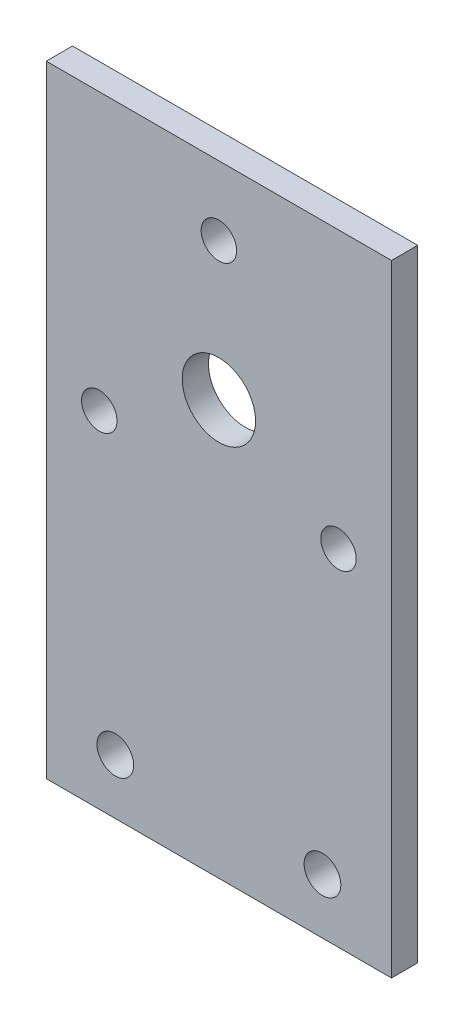
SolidWorks part; units mm, degrees
material "1060 Alloy"
ref_plane "Front Plane" through (0, 0, 0) normal (0, 0, 1) x (1, 0, 0)
ref_plane "Top Plane" through (0, 0, 0) normal (0, 1, 0) x (1, 0, 0)
ref_plane "Right Plane" through (0, 0, 0) normal (1, 0, 0) x (0, 0, -1)
sketch "Sketch1" plane through (0, 0, 0) normal (0, 0, 1) x (1, 0, 0)
  line L1 (0, 0) -> (63.5, 0)
  line L2 (0, 0) -> (0, 114.3)
  line L3 (0, 114.3) -> (63.5, 114.3)
  line L4 (63.5, 0) -> (63.5, 114.3)
  dimension "D1" = 114.3
  dimension "D2" = 63.5
extrude "Boss-Extrude1" add sketch "Sketch1" against normal blind 4.826
hole_wizard "F (0.257) Diameter Hole2" positions "Sketch9" profile "Sketch10" hole size "F" standard "ANSI Inch" end condition through all
sketch "Sketch9" plane through (0, 0, 0) normal (0, 0, 1) x (1, 0, 0)
  line L0 (0, 114.3) -> (0, 0) construction
  line L1 (0, 0) -> (63.5, 0) construction
  point P0 (12.7, 10.16)
  point P2 (50.8, 10.16)
  dimension "D1" = 12.7
  dimension "D2" = 10.16
  dimension "D3" = 50.8
sketch "Sketch10" plane through (12.7, 10.16, 0) normal (1, 0, 0) x (0, -1, 0)
  line L0 (0, 0) -> (0, 4.826)
  line L1 (0, 4.826) -> (3.3782, 4.826)
  line L2 (3.3782, 4.826) -> (3.3782, 0)
  line L5 (3.3782, 0) -> (0, 0)
  line L11 (0, -6.35) -> (0, 107.95) construction
  dimension "Thru Hole Dia." = 6.7564
  dimension "Thru Hole Depth" = 4.826
hole_wizard "F (0.257) Diameter Hole5" positions "Sketch18" profile "Sketch19" hole size "F" standard "ANSI Inch" end condition through all
sketch "Sketch18" plane through (0, 0, 0) normal (0, 0, 1) x (1, 0, 0)
  line L0 (0, 0) -> (63.5, 0) construction
  line L1 (0, 114.3) -> (0, 0) construction
  point P0 (31.75, 101.6)
  point P2 (9.7536, 63.5)
  point P4 (53.7464, 63.5)
  dimension "D1" = 101.6
  dimension "D2" = 31.75
  dimension "D3" = 63.5
  dimension "D4" = 9.7536
  dimension "D5" = 53.7464
sketch "Sketch19" plane through (31.75, 101.6, 0) normal (1, 0, 0) x (0, -1, 0)
  line L0 (0, 0) -> (0, 4.826)
  line L1 (0, 4.826) -> (3.2639, 4.826)
  line L2 (3.2639, 4.826) -> (3.2639, 0)
  line L5 (3.2639, 0) -> (0, 0)
  line L11 (0, -6.35) -> (0, 107.95) construction
  dimension "Thru Hole Dia." = 6.5278
  dimension "Thru Hole Depth" = 4.826
hole_wizard "17/32 (0.53125) Diameter Hole1" positions "Sketch20" profile "Sketch21" hole size "17/32" standard "ANSI Inch" end condition through all
sketch "Sketch20" plane through (0, 0, 0) normal (0, 0, 1) x (1, 0, 0)
  line L0 (0, 0) -> (63.5, 0) construction
  line L1 (0, 114.3) -> (0, 0) construction
  point P0 (31.75, 76.2)
  dimension "D1" = 76.2
  dimension "D2" = 31.75
sketch "Sketch21" plane through (31.75, 76.2, 0) normal (1, 0, 0) x (0, -1, 0)
  line L0 (0, 0) -> (0, 4.826)
  line L1 (0, 4.826) -> (6.7469, 4.826)
  line L2 (6.7469, 4.826) -> (6.7469, 0)
  line L5 (6.7469, 0) -> (0, 0)
  line L11 (0, -6.35) -> (0, 107.95) construction
  dimension "Thru Hole Dia." = 13.4937
  dimension "Thru Hole Depth" = 4.826
